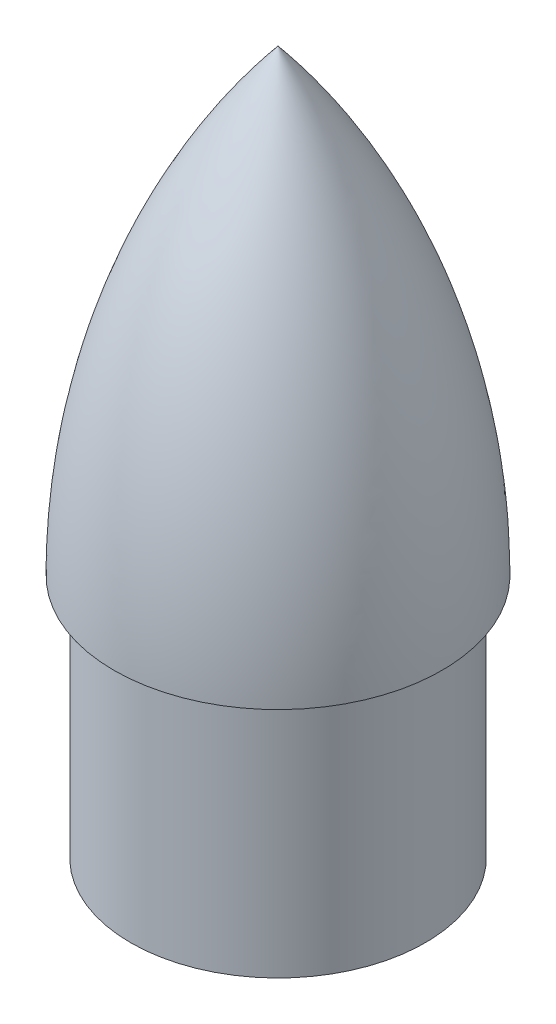
SolidWorks part; units mm, degrees
ref_plane "Front Plane" through (0, 0, 0) normal (0, 0, 1) x (1, 0, 0)
ref_plane "Top Plane" through (0, 0, 0) normal (0, 1, 0) x (1, 0, 0)
ref_plane "Right Plane" through (0, 0, 0) normal (1, 0, 0) x (0, 0, -1)
sketch "Sketch1" plane through (0, 0, 0) normal (1, 0, 0) x (0, 0, -1)
  line L0 (0, 0) -> (33.5709, 0)
  line L1 (55, 0) -> (-55, 0) construction
  line L2 (0, 0) -> (0, 93.9)
  arc A0 (33.5709, 0) -> (0, 93.9) centre (-114.5368, 0) ccw
  dimension "D1" = 33.5709
  dimension "D2" = 93.9
revolve "Revolve1" add sketch "Sketch1" angle 360 about L2
sketch "Sketch2" plane through (0, 0, 0) normal (0, -1, 0) x (1, 0, 0)
  circle A0 centre (0, 0) radius 30.15
  dimension "D1" = 60.3
extrude "Boss-Extrude1" add sketch "Sketch2" along normal blind 50
sketch "Sketch3" plane through (0, -50, 0) normal (0, -1, 0) x (1, 0, 0)
  circle A0 centre (0, 0) radius 27.75
  circle A1 centre (0, 0) radius 30.15 construction
  dimension "D1" = 2.4
extrude "Cut-Extrude1" cut sketch "Sketch3" against normal blind 63
chamfer "Chamfer1" distance 10 angle 51 1 edges at (0, 13, -27.75)
